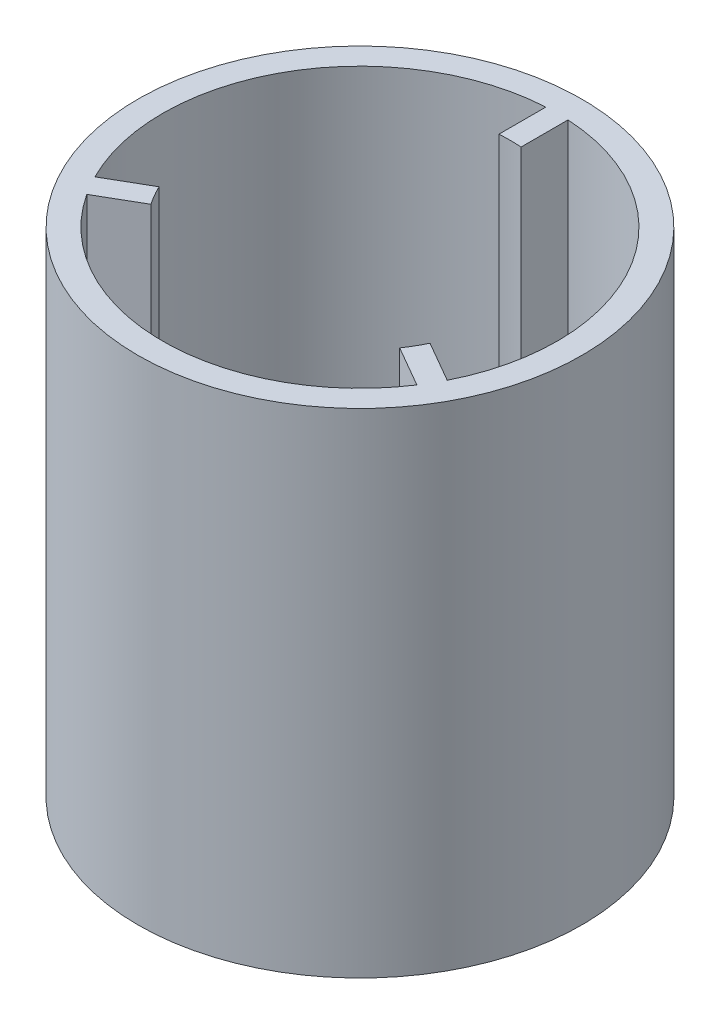
SolidWorks part; units mm, degrees
ref_plane "Front Plane" through (0, 0, 0) normal (0, 0, 1) x (1, 0, 0)
ref_plane "Top Plane" through (0, 0, 0) normal (0, 1, 0) x (1, 0, 0)
ref_plane "Right Plane" through (0, 0, 0) normal (1, 0, 0) x (0, 0, -1)
sketch "Sketch1" plane through (0, 0, 0) normal (0, 1, 0) x (1, 0, 0)
  circle A0 centre (0, 0) radius 4.5
  circle A1 centre (0, 0) radius 4
  dimension "D1" = 9
  dimension "D2" = 8
extrude "Boss-Extrude1" add sketch "Sketch1" along normal blind 10
sketch "Sketch2" plane through (0, 10, 0) normal (0, 1, 0) x (1, 0, 0)
  line L0 (0.1125, 0.1949) -> (4.0047, -2.0523)
  line L1 (-0.225, 0) -> (0.225, 0)
  line L2 (-0.225, 0) -> (-0.225, 4.4944)
  line L3 (-0.225, 4.4944) -> (0.225, 4.4944)
  line L4 (0.225, 0) -> (0.225, 4.4944)
  line L5 (0.1125, 0.1949) -> (-0.1125, -0.1949)
  line L6 (-0.1125, -0.1949) -> (3.7797, -2.442)
  line L7 (4.0047, -2.0523) -> (3.7797, -2.442)
  line L8 (0.1125, -0.1949) -> (-3.7797, -2.442)
  line L9 (0.1125, -0.1949) -> (-0.1125, 0.1949)
  line L10 (-0.1125, 0.1949) -> (-4.0047, -2.0523)
  line L11 (-3.7797, -2.442) -> (-4.0047, -2.0523)
  circle A0 centre (0, 0) radius 4.5 construction
  circle A1 centre (0, 0) radius 3.05
  point P8 (0, 0)
  point P10 (0, 0)
  point P18 (0, 0)
  circle M6 centre (0, 0) radius 4
  dimension "D3" = 6.1
  dimension "D1" = 0.45
  dimension "D2" = 3
extrude "Boss-Extrude2" add sketch "Sketch2" against normal blind 10 contours A1 L4 L2 M6 | A1 L6 L0 M6 | A1 L10 L8 M6
